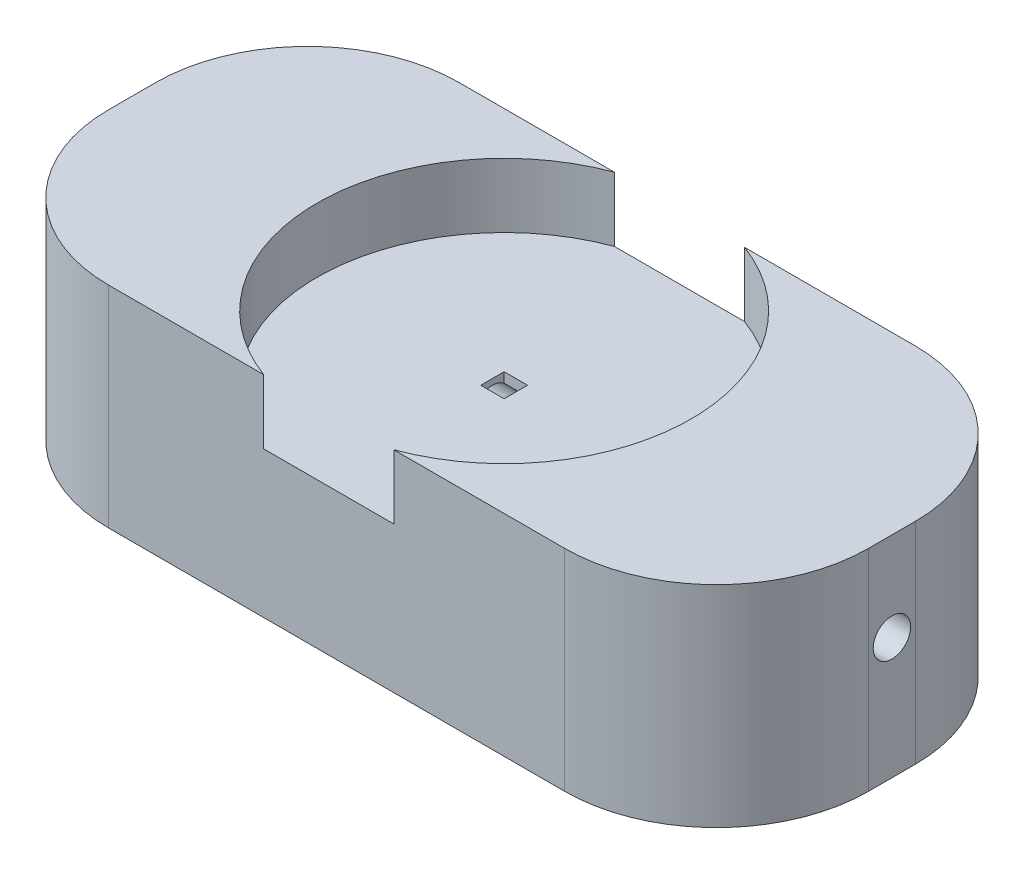
SolidWorks part; units mm, degrees
ref_plane "Front Plane" through (0, 0, 0) normal (0, 0, 1) x (1, 0, 0)
ref_plane "Top Plane" through (0, 0, 0) normal (0, 1, 0) x (1, 0, 0)
ref_plane "Right Plane" through (0, 0, 0) normal (1, 0, 0) x (0, 0, -1)
sketch "Sketch1" plane through (0, 0, 0) normal (0, 1, 0) x (1, 0, 0)
  line L1 (-25, -15) -> (40, -15)
  line L2 (-25, -15) -> (-25, 15)
  line L3 (-25, 15) -> (40, 15)
  line L4 (40, -15) -> (40, 15)
  line L5 (-25, -15) -> (40, 15) construction
  line L6 (-25, 15) -> (40, -15) construction
  point P0 (0, 0)
  dimension "D1" = 30
  dimension "D2" = 65
extrude "Boss-Extrude1" add sketch "Sketch1" along normal blind 58
sketch "Sketch3" plane through (-25, 0, 0) normal (-1, 0, 0) x (0, 0, 1)
  line L0 (-15, 58) -> (15, 58) construction
  circle A0 centre (0, 50.4) radius 1.6
  dimension "D1" = 3.2
  dimension "D2" = 7.6
fillet "Fillet1" radius 13 4 edges at (40, 29, -15) (-25, 29, -15) (40, 29, 15) (-25, 29, 15)
ref_plane "Plane2" through (0, -10, 0) normal (0, -1, 0) x (-1, 0, 0)
sketch "Sketch15" plane through (0, -10, 0) normal (0, -1, 0) x (-1, 0, 0)
  line L1 (-41.9055, 15.8797) -> (41.7906, 15.8797)
  line L2 (-41.9055, 15.8797) -> (-41.9055, -15.8187)
  line L3 (-41.9055, -15.8187) -> (41.7906, -15.8187)
  line L4 (41.7906, 15.8797) -> (41.7906, -15.8187)
extrude "Cut-Extrude7" cut sketch "Sketch15" against normal blind 50
ref_plane "Plane3" through (0, 40, 0) normal (0, -1, 0) x (-1, 0, 0)
ref_plane "Plane4" through (0, 58, 0) normal (0, 1, 0) x (1, 0, 0)
sketch "Sketch18" plane through (0, 58, 0) normal (0, 1, 0) x (1, 0, 0)
  circle A0 centre (6.8285, 0) radius 16
  dimension "D1" = 32
extrude "Cut-Extrude10" cut sketch "Sketch18" against normal blind 5.5
extrude "Cut-Extrude12" cut sketch "Sketch3" against normal through all
ref_plane "Plane5" through (0, 52.5, 0) normal (0, 1, 0) x (1, 0, 0)
sketch "Sketch21" plane through (0, 52.5, 0) normal (0, 1, 0) x (1, 0, 0)
  line L1 (5.8285, -1) -> (7.8285, -1)
  line L2 (5.8285, -1) -> (5.8285, 1)
  line L3 (5.8285, 1) -> (7.8285, 1)
  line L4 (7.8285, -1) -> (7.8285, 1)
  line L5 (5.8285, -1) -> (7.8285, 1) construction
  line L6 (5.8285, 1) -> (7.8285, -1) construction
  point P0 (6.8285, 0)
  dimension "D1" = 2
  dimension "D2" = 2
extrude "Cut-Extrude13" cut sketch "Sketch21" against normal blind 8
